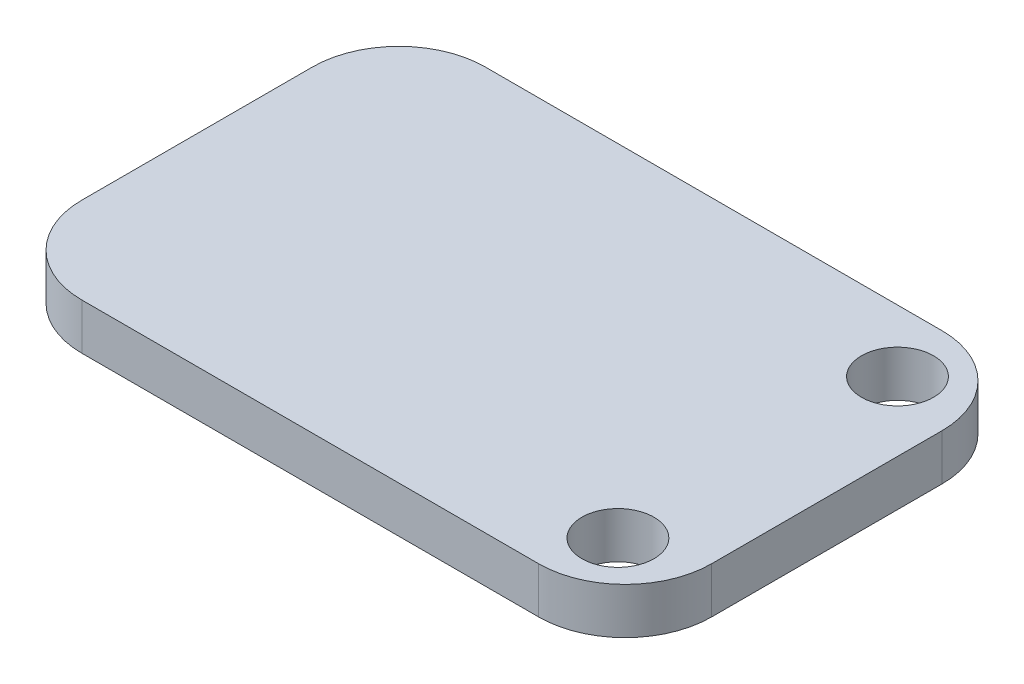
SolidWorks part; units mm, degrees
material "PBT General Purpose"
ref_plane "Front Plane" through (0, 0, 0) normal (0, 0, 1) x (1, 0, 0)
ref_plane "Top Plane" through (0, 0, 0) normal (0, 1, 0) x (1, 0, 0)
ref_plane "Right Plane" through (0, 0, 0) normal (1, 0, 0) x (0, 0, -1)
sketch "Sketch1" plane through (0, 0, 0) normal (0, 1, 0) x (1, 0, 0)
  line L1 (-11.1, 7) -> (4.75, 7)
  line L2 (-14.1, 4) -> (-14.1, -4)
  line L3 (-11.1, -7) -> (4.75, -7)
  line L4 (7.75, 4) -> (7.75, -4)
  arc A0 (-11.1, 7) -> (-14.1, 4) centre (-11.1, 4) ccw
  arc A1 (-14.1, -4) -> (-11.1, -7) centre (-11.1, -4) ccw
  arc A2 (4.75, -7) -> (7.75, -4) centre (4.75, -4) ccw
  arc A3 (4.75, 7) -> (7.75, 4) centre (4.75, 4) cw
  circle A4 centre (5.35, 4.85) radius 1.25
  circle A5 centre (5.35, -4.85) radius 1.25
  point P7 (-14.1, 7)
  point P12 (7.75, -7)
  point P15 (7.75, 7)
  dimension "D5" = 3
  dimension "D9" = 2.5
  dimension "D1" = 14
  dimension "D2" = 7
  dimension "D3" = 21.85
  dimension "D4" = 7.75
  dimension "D6" = 2.15
  dimension "D7" = 9.7
  dimension "D8" = 2.4
extrude "Boss-Extrude1" add sketch "Sketch1" against normal blind 1.6
